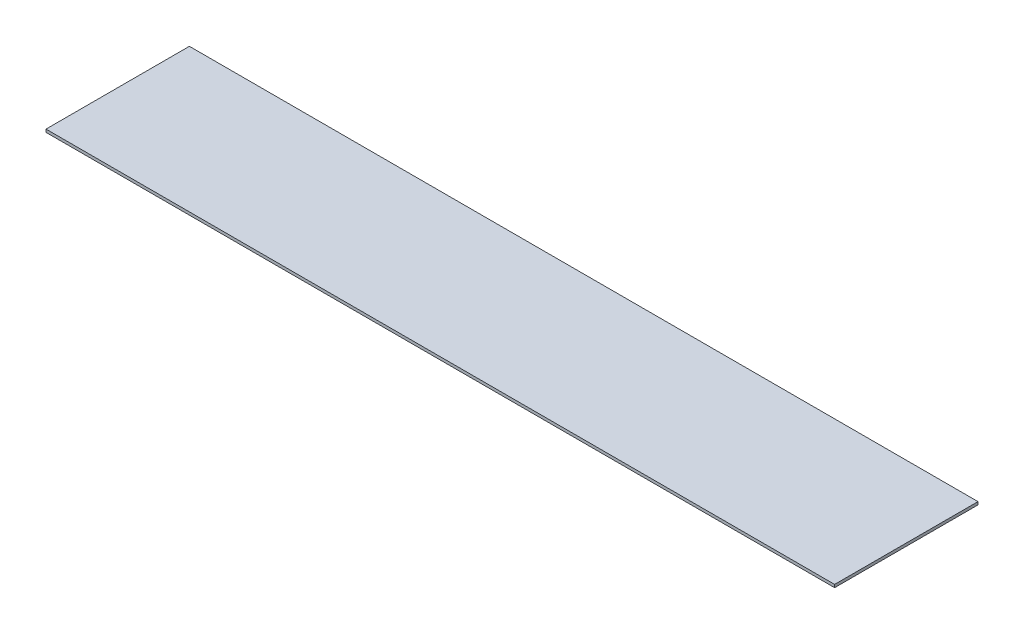
SolidWorks part; units mm, degrees
material "Cast Alloy Steel"
ref_plane "Front Plane" through (0, 0, 0) normal (0, 0, 1) x (1, 0, 0)
ref_plane "Top Plane" through (0, 0, 0) normal (0, 1, 0) x (1, 0, 0)
ref_plane "Right Plane" through (0, 0, 0) normal (1, 0, 0) x (0, 0, -1)
sketch "Sketch1" plane through (0, 0, 0) normal (0, 1, 0) x (1, 0, 0)
  line L1 (-34.925, -6.35) -> (34.925, -6.35)
  line L2 (-34.925, -6.35) -> (-34.925, 6.35)
  line L3 (-34.925, 6.35) -> (34.925, 6.35)
  line L4 (34.925, -6.35) -> (34.925, 6.35)
  line L5 (-34.925, -6.35) -> (34.925, 6.35) construction
  line L6 (-34.925, 6.35) -> (34.925, -6.35) construction
  point P0 (0, 0)
  dimension "D1" = 69.85
  dimension "D2" = 12.7
extrude "Boss-Extrude1" add sketch "Sketch1" along normal blind 0.254
